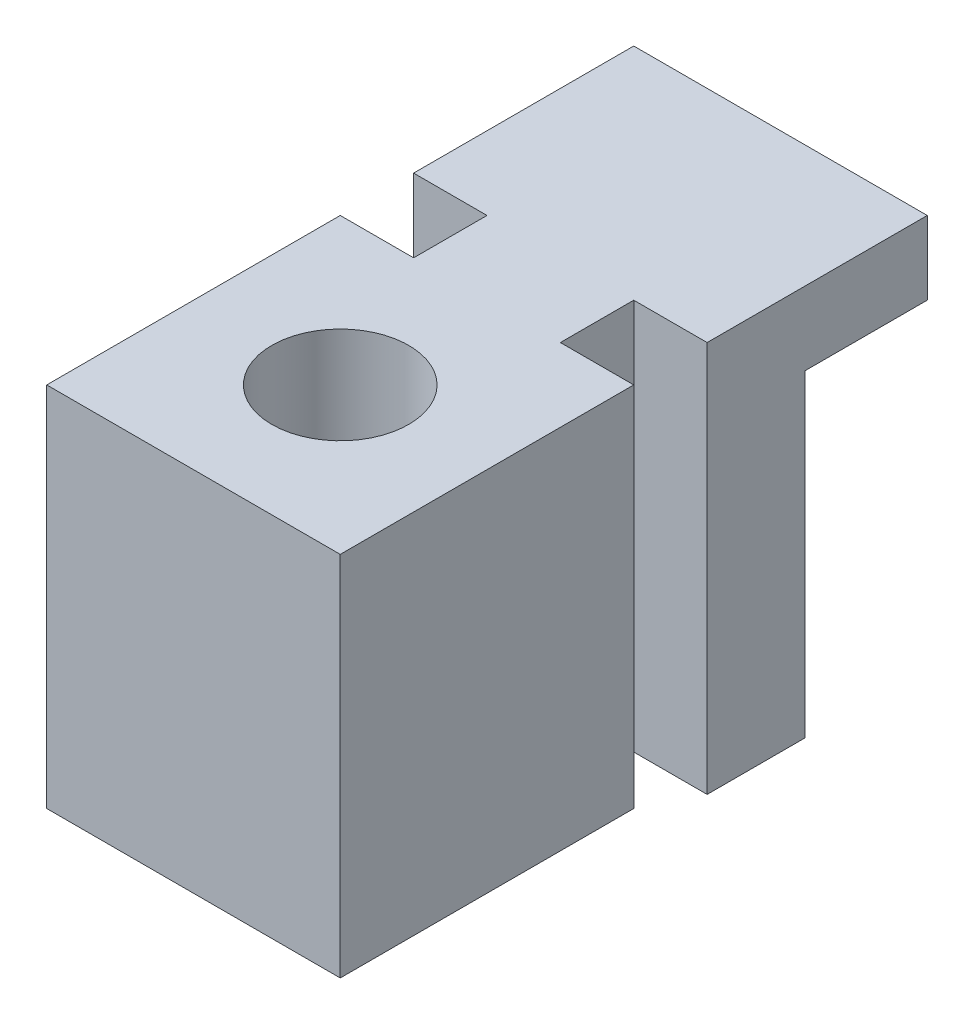
SolidWorks part; units mm, degrees
ref_plane "Front Plane" through (0, 0, 0) normal (0, 0, 1) x (1, 0, 0)
ref_plane "Top Plane" through (0, 0, 0) normal (0, 1, 0) x (1, 0, 0)
ref_plane "Right Plane" through (0, 0, 0) normal (1, 0, 0) x (0, 0, -1)
sketch "Sketch3" plane through (0, 0, 0) normal (0, 0, 1) x (1, 0, 0)
  line L1 (-3, 3.25) -> (3, 3.25)
  line L2 (-3, 3.25) -> (-3, -3.25)
  line L3 (-3, -3.25) -> (3, -3.25)
  line L4 (3, 3.25) -> (3, -3.25)
  line L5 (-3, 3.25) -> (3, -3.25) construction
  line L6 (-3, -3.25) -> (3, 3.25) construction
  point P0 (0, 0)
  dimension "D1" = 6.5
  dimension "D2" = 6
extrude "Boss-Extrude3" add sketch "Sketch3" along normal blind 2
sketch "Sketch4" plane through (0, 3.25, 0) normal (0, 1, 0) x (1, 0, 0)
  line L0 (0, 0) -> (0, -4.0005) construction
  line L1 (3, -2) -> (-3, -2) construction
  line L2 (1.5, -3.5) -> (-1.5, -3.5)
  line L3 (1.5, -3.5) -> (1.5, -2)
  line L4 (1.5, -2) -> (-1.5, -2)
  line L5 (-1.5, -3.5) -> (-1.5, -2)
  line L6 (1.5, -3.5) -> (-1.5, -2) construction
  line L7 (1.5, -2) -> (-1.5, -3.5) construction
  point P3 (0, -2.75)
  dimension "D1" = 3
  dimension "D2" = 1.5
extrude "Boss-Extrude4" add sketch "Sketch4" against normal blind 6
sketch "Sketch5" plane through (0, 3.25, 0) normal (0, 1, 0) x (1, 0, 0)
  line L0 (-1.5, -3.5) -> (1.5, -3.5) construction
  line L1 (-3, -3.5) -> (3, -3.5)
  line L2 (-3, -3.5) -> (-3, -9.5)
  line L3 (-3, -9.5) -> (3, -9.5)
  line L4 (3, -3.5) -> (3, -9.5)
  line L5 (0, 0) -> (0, -3.5) construction
  line L6 (-3, -6.5) -> (3, -6.5) construction
  circle A0 centre (0, -6.5) radius 1.4
  point P10 (0, -3.5)
  dimension "D3" = 2.8
  dimension "D1" = 6
  dimension "D2" = 6
extrude "Boss-Extrude5" add sketch "Sketch5" against normal blind 6
sketch "Sketch9" plane through (0, 3.25, 0) normal (0, 1, 0) x (1, 0, 0)
  line L0 (3, -9.5) -> (-3, -9.5)
  line L1 (-3, -9.5) -> (-3, -3.5)
  line L2 (-3, -3.5) -> (-1.5, -3.5)
  line L3 (-1.5, -3.5) -> (-1.5, -2)
  line L4 (-1.5, -2) -> (-3, -2)
  line L5 (-3, -2) -> (-3, 0)
  line L6 (-3, 0) -> (3, 0)
  line L7 (3, 0) -> (3, -2)
  line L8 (3, -2) -> (1.5, -2)
  line L9 (1.5, -2) -> (1.5, -3.5)
  line L10 (1.5, -3.5) -> (3, -3.5)
  line L11 (3, -3.5) -> (3, -9.5)
  line L12 (-1.4, -6.5) -> (1.4, -6.5) construction
  circle A0 centre (0, -6.5) radius 1.4 construction
  circle A1 centre (0, -6.5) radius 1.4
extrude "Boss-Extrude6" add sketch "Sketch9" along normal blind 1.5
sketch "Sketch10" plane through (0, 0, 0) normal (0, 0, -1) x (-1, 0, 0)
  line L0 (3, 4.75) -> (3, -3.25) construction
  line L1 (-3, 4.75) -> (3, 4.75)
  line L2 (-3, 4.75) -> (-3, 3.25)
  line L3 (-3, 3.25) -> (3, 3.25)
  line L4 (3, 4.75) -> (3, 3.25)
  dimension "D1" = 1.5
extrude "Boss-Extrude7" add sketch "Sketch10" along normal blind 2.5
